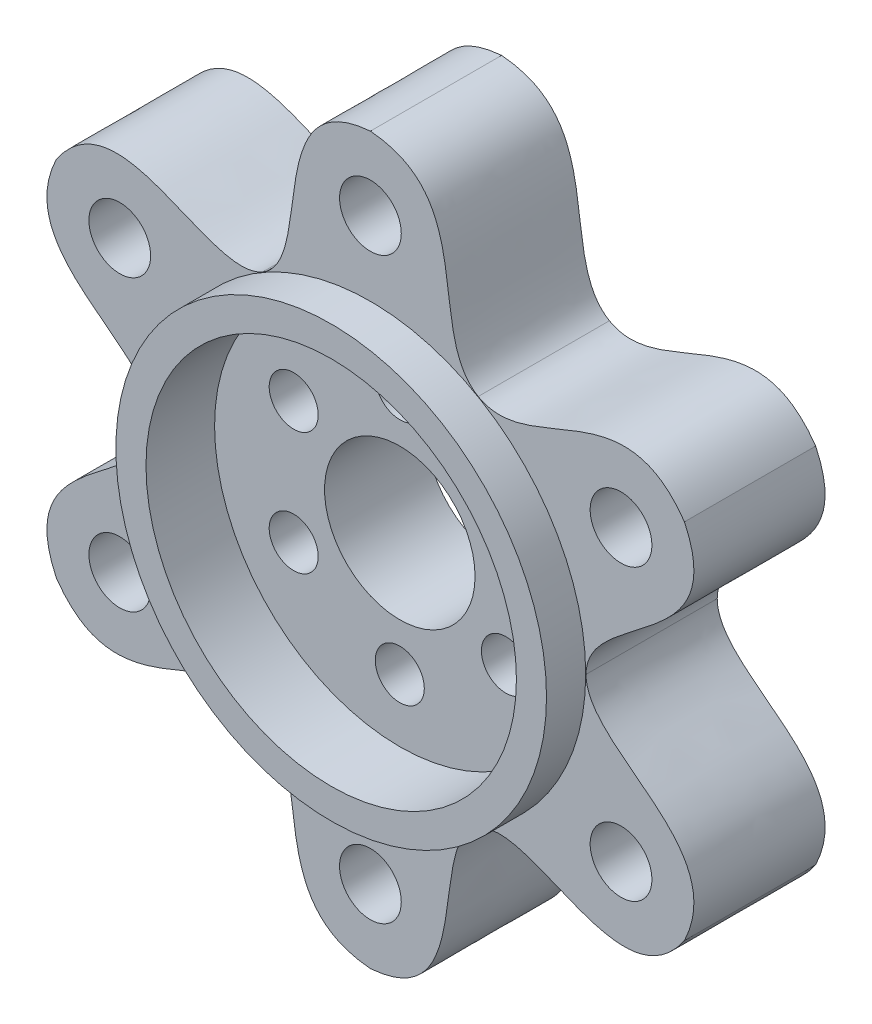
SolidWorks part; units mm, degrees
material "7075-T6 (SN)"
ref_plane "Front Plane" through (0, 0, 0) normal (0, 0, 1) x (1, 0, 0)
ref_plane "Top Plane" through (0, 0, 0) normal (0, 1, 0) x (1, 0, 0)
ref_plane "Right Plane" through (0, 0, 0) normal (1, 0, 0) x (0, 0, -1)
sketch "Sketch1" plane through (0, 0, 0) normal (0, 0, 1) x (1, 0, 0)
  line L0 (0, 0) -> (0, 37.5) construction
  circle A0 centre (0, 0) radius 46.99
  circle A11 centre (0, 15.875) radius 3.175
  circle A13 centre (0, 0) radius 9.75
  circle A14 centre (0, 37.5) radius 4
  circle A15 centre (-32.476, 18.75) radius 4
  circle A16 centre (-32.476, -18.75) radius 4
  circle A17 centre (32.476, 18.75) radius 4
  circle A18 centre (32.476, -18.75) radius 4
  circle A19 centre (0, -37.5) radius 4
  circle A21 centre (0, 0) radius 37.5 construction
  circle A25 centre (13.7482, 7.9375) radius 3.175
  circle A26 centre (13.7482, -7.9375) radius 3.175
  circle A27 centre (0, -15.875) radius 3.175
  circle A28 centre (-13.7482, -7.9375) radius 3.175
  circle A29 centre (-13.7482, 7.9375) radius 3.175
  point P5 (18.9797, -2.1706)
  point P16 (0, 0)
  point P17 (0, 0)
  point P30 (0, 0)
  dimension "D2" = 6.35
  dimension "D3" = 8
  dimension "D4" = 75
  dimension "D11" = 93.98
  dimension "D14" = 19.5
  dimension "D5" = 37.5
  dimension "D6" = 37.5
  dimension "D7" = 37.5
  dimension "D8" = 37.5
  dimension "D9" = 37.5
  dimension "D10" = 37.5
  dimension "D12" = 15.875
  dimension "D13" = 6
extrude "Boss-Extrude1" add sketch "Sketch1" along normal blind 17 contours A0
sketch "Sketch3" plane through (0, 0, 17) normal (0, 0, 1) x (1, 0, 0)
  line L0 (0, 0) -> (0, 46.99) construction
  line L1 (0, 0) -> (13.97, 24.1967) construction
  line L2 (41.9161, 34.0781) -> (41.9161, -28.2115) construction
  line L3 (-41.9161, 39.087) -> (-41.9161, -25.2539) construction
  circle A0 centre (0, 0) radius 46.99 construction
  circle A1 centre (0, 0) radius 27.94 construction
  spline S0 degree 3 poles (0, 46.99) (14.2042, 45.8473) (7.0459, 28.2576) (13.97, 24.1967) knots 0 0 0 0 1 1 1 1
  spline S1 degree 3 poles (0, 46.99) (-14.2042, 45.8473) (-7.0459, 28.2576) (-13.97, 24.1967) knots 0 0 0 0 1 1 1 1
  spline S2 degree 3 poles (40.6945, 23.495) (46.807, 10.6225) (27.9947, 8.0269) (27.94, 0) knots 0 0 0 0 1 1 1 1
  spline S3 degree 3 poles (40.6945, 23.495) (32.6028, 35.2248) (20.9488, 20.2307) (13.97, 24.1967) knots 0 0 0 0 1 1 1 1
  spline S4 degree 3 poles (40.6945, -23.495) (32.6028, -35.2248) (20.9488, -20.2307) (13.97, -24.1967) knots 0 0 0 0 1 1 1 1
  spline S5 degree 3 poles (40.6945, -23.495) (46.807, -10.6225) (27.9947, -8.0269) (27.94, 0) knots 0 0 0 0 1 1 1 1
  spline S6 degree 3 poles (0, -46.99) (-14.2042, -45.8473) (-7.0459, -28.2576) (-13.97, -24.1967) knots 0 0 0 0 1 1 1 1
  spline S7 degree 3 poles (0, -46.99) (14.2042, -45.8473) (7.0459, -28.2576) (13.97, -24.1967) knots 0 0 0 0 1 1 1 1
  spline S8 degree 3 poles (-40.6945, -23.495) (-46.807, -10.6225) (-27.9947, -8.0269) (-27.94, 0) knots 0 0 0 0 1 1 1 1
  spline S9 degree 3 poles (-40.6945, -23.495) (-32.6028, -35.2248) (-20.9488, -20.2307) (-13.97, -24.1967) knots 0 0 0 0 1 1 1 1
  spline S10 degree 3 poles (-40.6945, 23.495) (-32.6028, 35.2248) (-20.9488, 20.2307) (-13.97, 24.1967) knots 0 0 0 0 1 1 1 1
  spline S11 degree 3 poles (-40.6945, 23.495) (-46.807, 10.6225) (-27.9947, 8.0269) (-27.94, 0) knots 0 0 0 0 1 1 1 1
  point P26 (0, 0)
  circle M18 centre (0, 0) radius 46.99
extrude "Cut-Extrude2" cut sketch "Sketch3" against normal through all contours S10 S1 M18 | S3 S0 M18 | S5 S2 M18 | S7 S4 M18 | S9 S6 M18 | S11 S8 M18
sketch "Sketch5" plane through (0, 0, 17) normal (0, 0, 1) x (1, 0, 0)
  line L0 (0, 0) -> (0, 27.94) construction
  line L1 (0, 0) -> (10.414, 18.0376) construction
  circle A0 centre (0, 0) radius 20.828 construction
  circle A1 centre (0, 0) radius 27.94 construction
  spline S0 degree 3 poles (0, 27.94) (7.52, 27.94) (6.3689, 20.373) (10.414, 18.0376) knots 0 0 0 0 1 1 1 1
  spline S1 degree 3 poles (0, 27.94) (-7.52, 27.94) (-6.3689, 20.373) (-10.414, 18.0376) knots 0 0 0 0 1 1 1 1
  spline S2 degree 3 poles (24.1967, 13.97) (27.9567, 7.4575) (20.828, 4.6709) (20.828, 0) knots 0 0 0 0 1 1 1 1
  spline S3 degree 3 poles (24.1967, 13.97) (20.4368, 20.4825) (14.4591, 15.7021) (10.414, 18.0376) knots 0 0 0 0 1 1 1 1
  spline S4 degree 3 poles (24.1967, -13.97) (20.4368, -20.4825) (14.4591, -15.7021) (10.414, -18.0376) knots 0 0 0 0 1 1 1 1
  spline S5 degree 3 poles (24.1967, -13.97) (27.9567, -7.4575) (20.828, -4.6709) (20.828, 0) knots 0 0 0 0 1 1 1 1
  spline S6 degree 3 poles (0, -27.94) (-7.52, -27.94) (-6.3689, -20.373) (-10.414, -18.0376) knots 0 0 0 0 1 1 1 1
  spline S7 degree 3 poles (0, -27.94) (7.52, -27.94) (6.3689, -20.373) (10.414, -18.0376) knots 0 0 0 0 1 1 1 1
  spline S8 degree 3 poles (-24.1967, -13.97) (-27.9567, -7.4575) (-20.828, -4.6709) (-20.828, 0) knots 0 0 0 0 1 1 1 1
  spline S9 degree 3 poles (-24.1967, -13.97) (-20.4368, -20.4825) (-14.4591, -15.7021) (-10.414, -18.0376) knots 0 0 0 0 1 1 1 1
  spline S10 degree 3 poles (-24.1967, 13.97) (-20.4368, 20.4825) (-14.4591, 15.7021) (-10.414, 18.0376) knots 0 0 0 0 1 1 1 1
  spline S11 degree 3 poles (-24.1967, 13.97) (-27.9567, 7.4575) (-20.828, 4.6709) (-20.828, 0) knots 0 0 0 0 1 1 1 1
  point P24 (0, 0)
  point P30 (0, 0)
  point P39 (0, 0)
ref_plane "Plane1" through (-41.9161, 0, 0) normal (-1, 0, 0) x (0, -1, 0)
sketch "Sketch7" plane through (0, 0, 17) normal (0, 0, 1) x (1, 0, 0)
  circle A0 centre (0, 0) radius 27.9
  circle A1 centre (0, 0) radius 24
  dimension "D1" = 55.8
  dimension "D2" = 48
extrude "Boss-Extrude2" add sketch "Sketch7" along normal blind 5.08 and the other way up to next (17 mm away)
sketch "Sketch8" plane through (0, 0, 17) normal (0, 0, 1) x (1, 0, 0)
  circle A0 centre (0, 0) radius 24
  dimension "D1" = 48
extrude "Cut-Extrude3" cut sketch "Sketch8" against normal blind 3.81
